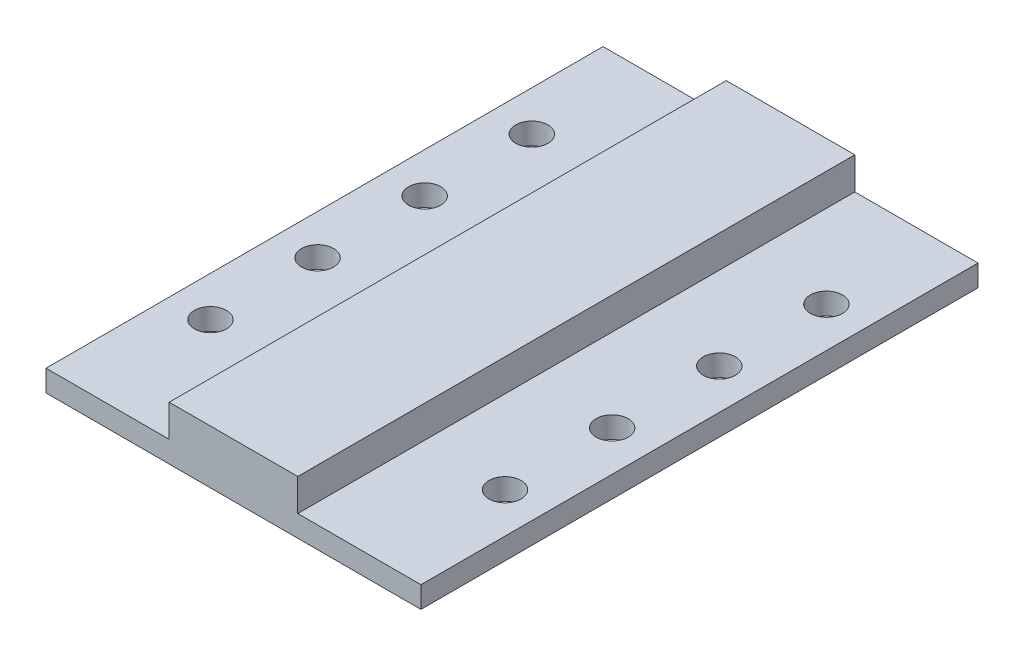
SolidWorks part; units mm, degrees
ref_plane "Спереди" through (0, 0, 0) normal (0, 0, 1) x (1, 0, 0)
ref_plane "Сверху" through (0, 0, 0) normal (0, 1, 0) x (1, 0, 0)
ref_plane "Справа" through (0, 0, 0) normal (1, 0, 0) x (0, 0, -1)
sketch "Эскиз1" plane through (0, 0, 0) normal (0, 1, 0) x (1, 0, 0)
  line L0 (17.5, -26) -> (-17.5, -26)
  line L1 (17.5, -26) -> (17.5, 26)
  line L2 (17.5, 26) -> (-17.5, 26)
  line L3 (-17.5, -26) -> (-17.5, 26)
extrude "Бобышка-Вытянуть1" add sketch "Эскиз1" along normal blind 2
sketch "Эскиз2" plane through (0, 0, 0) normal (0, 0, 1) x (1, 0, 0)
  line L0 (-17.5, 2) -> (17.5, 2) construction
  line L1 (-6, 2) -> (6, 2)
  line L2 (-6, 2) -> (-6, 5)
  line L3 (-6, 5) -> (6, 5)
  line L4 (6, 2) -> (6, 5)
  line L7 (0, 5) -> (0, 2) construction
  line L8 (0, 0) -> (0, 2) construction
  line L9 (-17.5, 0) -> (17.5, 0) construction
  dimension "D1" = 0
  dimension "D2" = 12
  dimension "D3" = 3
extrude "Бобышка-Вытянуть2" add sketch "Эскиз2" along normal up to surface and the other way up to surface up to face at (0, 1, 26) other way up to face at (0, 1, -26)
sketch "Эскиз3" plane through (0, 2, 0) normal (0, 1, 0) x (1, 0, 0)
  line L0 (0, 26) -> (0, -26) construction
  line L5 (-6, 26) -> (6, 26) construction
  line L6 (-6, -26) -> (6, -26) construction
  circle A0 centre (13.75, 15.6) radius 1.5
  circle A1 centre (-13.75, 15.6) radius 1.5
  circle A2 centre (-13.75, 5.6) radius 1.5
  circle A3 centre (13.75, 5.6) radius 1.5
  circle A4 centre (-13.75, -4.4) radius 1.5
  circle A5 centre (13.75, -4.4) radius 1.5
  circle A6 centre (-13.75, -14.4) radius 1.5
  circle A7 centre (13.75, -14.4) radius 1.5
  dimension "D1" = 4
extrude "Вырез-Вытянуть1" cut sketch "Эскиз3" against normal blind 10
